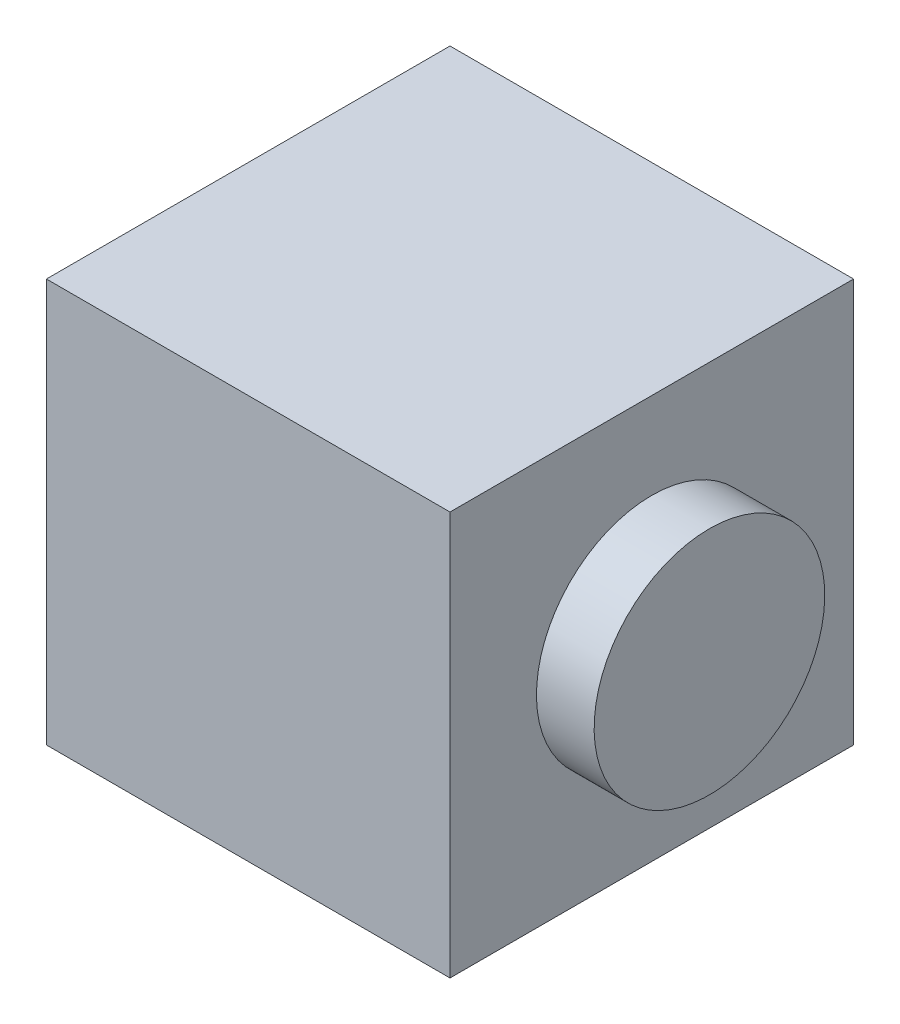
SolidWorks part; units mm, degrees
ref_plane "Alzado" through (0, 0, 0) normal (0, 0, 1) x (1, 0, 0)
ref_plane "Planta" through (0, 0, 0) normal (0, 1, 0) x (1, 0, 0)
ref_plane "Vista lateral" through (0, 0, 0) normal (1, 0, 0) x (0, 0, -1)
sketch "Croquis1" plane through (0, 0, 0) normal (0, 0, 1) x (1, 0, 0)
  line L1 (0, 0) -> (70, 0)
  line L2 (0, 0) -> (0, 70)
  line L3 (0, 70) -> (70, 70)
  line L4 (70, 0) -> (70, 70)
  dimension "D1" = 70
  dimension "D2" = 70
extrude "Saliente-Extruir1" add sketch "Croquis1" along normal blind 70
sketch "Croquis2" plane through (70, 0, 0) normal (1, 0, 0) x (0, 0, -1)
  circle A0 centre (-35, 35) radius 20
  point P5 (0, 0)
  dimension "D1" = 40
  dimension "D2" = 35
  dimension "D3" = 35
extrude "Saliente-Extruir2" add sketch "Croquis2" along normal blind 10
sketch "Croquis3" plane through (0, 0, 0) normal (0, 0, -1) x (-1, 0, 0)
  circle A0 centre (-35, 35) radius 20
  dimension "D1" = 40
  dimension "D2" = 35
  dimension "D3" = 35
extrude "Cortar-Extruir1" cut sketch "Croquis3" against normal blind 10
